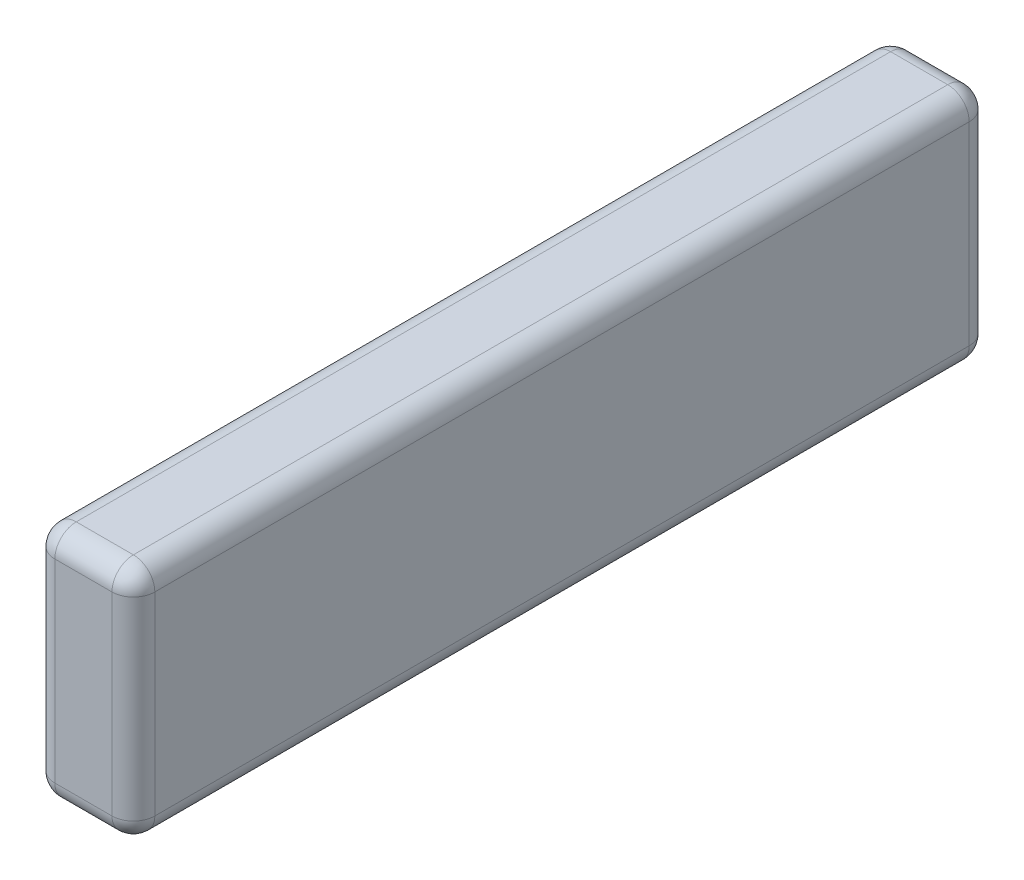
SolidWorks part; units mm, degrees
ref_plane "Front Plane" through (0, 0, 0) normal (0, 0, 1) x (1, 0, 0)
ref_plane "Top Plane" through (0, 0, 0) normal (0, 1, 0) x (1, 0, 0)
ref_plane "Right Plane" through (0, 0, 0) normal (1, 0, 0) x (0, 0, -1)
sketch "Sketch1" plane through (0, 0, 0) normal (1, 0, 0) x (0, 0, -1)
  line L1 (600, 165.8) -> (-600, 165.8)
  line L2 (600, 165.8) -> (600, -165.8)
  line L3 (600, -165.8) -> (-600, -165.8)
  line L4 (-600, 165.8) -> (-600, -165.8)
  line L5 (600, 165.8) -> (-600, -165.8) construction
  line L6 (600, -165.8) -> (-600, 165.8) construction
  point P0 (0, 0)
  dimension "D1" = 1200
  dimension "D2" = 331.6
extrude "Boss-Extrude1" add sketch "Sketch1" along normal blind 140
fillet "Fillet1" radius 30 12 edges at (70, -165.8, 600) (70, -165.8, -600) (70, 165.8, -600) (70, 165.8, 600) (0, -165.8, 0) (0, 0, -600) (0, 165.8, 0) (0, 0, 600) (140, 165.8, 0) (140, 0, -600) (140, -165.8, 0) (140, 0, 600)
